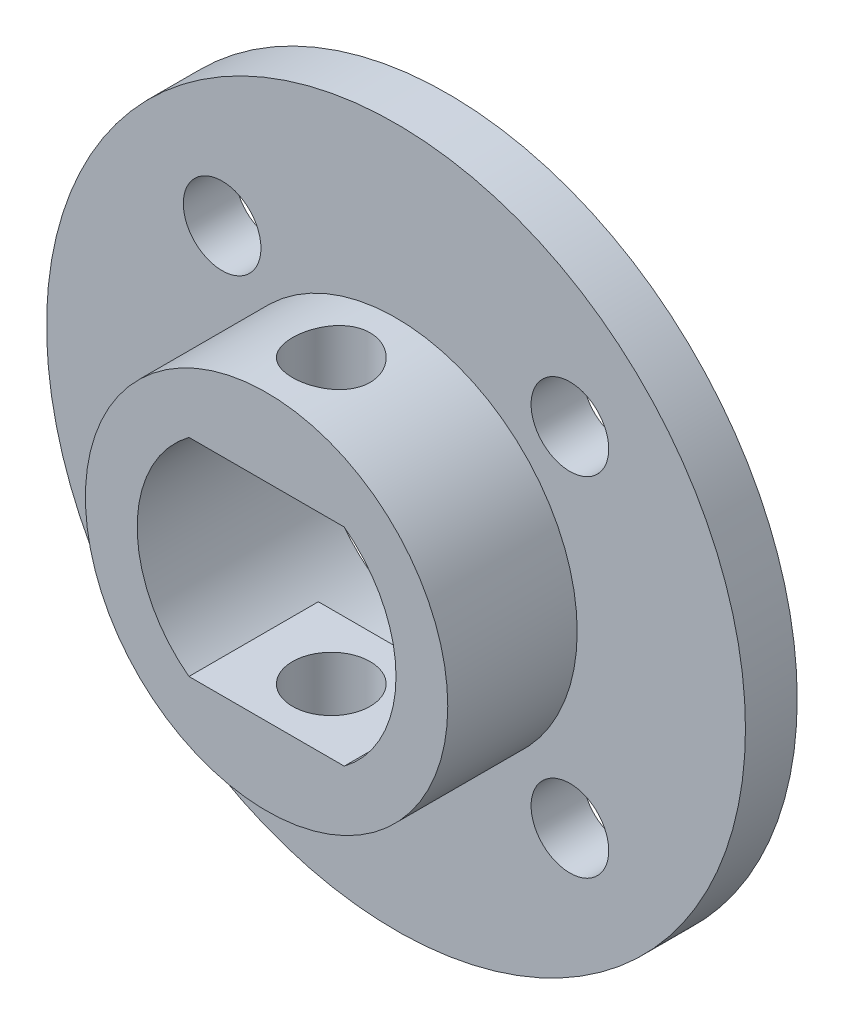
SolidWorks part; units mm, degrees
material "镀铬不锈钢"
ref_plane "前视基准面" through (0, 0, 0) normal (0, 0, 1) x (1, 0, 0)
ref_plane "上视基准面" through (0, 0, 0) normal (0, 1, 0) x (1, 0, 0)
ref_plane "右视基准面" through (0, 0, 0) normal (1, 0, 0) x (0, 0, -1)
sketch "草图1" plane through (0, 0, 0) normal (0, 0, 1) x (1, 0, 0)
  line L0 (9.5, 0) -> (0, 0) construction
  line L1 (0, 0) -> (6.7175, 6.7175) construction
  circle A0 centre (0, 0) radius 9.5 construction
  circle A1 centre (0, 0) radius 13.5
  circle A6 centre (6.7175, 6.7175) radius 1.5
  circle A7 centre (6.7175, -6.7175) radius 1.5
  circle A8 centre (-6.7175, -6.7175) radius 1.5
  circle A9 centre (-6.7175, 6.7175) radius 1.5
  point P15 (0, 0)
  point P17 (0, 0)
  dimension "D1" = 19
  dimension "D2" = 27
  dimension "D3" = 3
  dimension "D4" = 45
  dimension "D5" = 4
extrude "凸台-拉伸1" add sketch "草图1" along normal blind 2
sketch "草图2" plane through (0, 0, 2) normal (0, 0, 1) x (1, 0, 0)
  circle A0 centre (0, 0) radius 7
  dimension "D1" = 14
extrude "凸台-拉伸2" add sketch "草图2" along normal blind 5
sketch "草图3" plane through (0, 0, 7) normal (0, 0, 1) x (1, 0, 0)
  line L0 (-3, 4) -> (3, 4)
  line L1 (-3, -4) -> (3, -4)
  arc A0 (3, -4) -> (3, 4) centre (0, 0) ccw
  arc A1 (-3, 4) -> (-3, -4) centre (0, 0) ccw
  dimension "D1" = 10
  dimension "D2" = 4
  dimension "D3" = 4
extrude "切除-拉伸1" cut sketch "草图3" against normal through all
sketch "草图4" plane through (0, 4, 0) normal (0, -1, 0) x (1, 0, 0)
  line L0 (-3, 0) -> (-3, 7) construction
  line L2 (3, 7) -> (-3, 7) construction
  circle A0 centre (0, 4.5) radius 1.5
  dimension "D1" = 3
  dimension "D2" = 3
  dimension "D3" = 2.5
extrude "切除-拉伸2" cut sketch "草图4" against normal through all and the other way through all
sketch "草图5" plane through (0, 0, 0) normal (0, 0, -1) x (-1, 0, 0)
  circle A0 centre (0, 0) radius 5
  dimension "D1" = 10
extrude "切除-拉伸3" cut sketch "草图5" against normal blind 2
